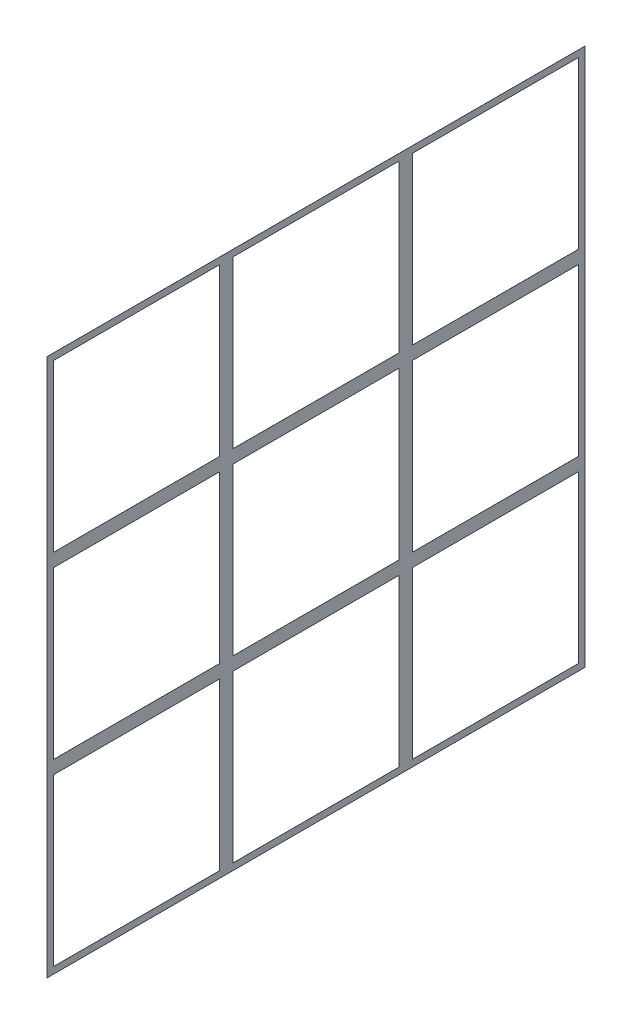
SolidWorks part; units mm, degrees
ref_plane "前视基准面" through (0, 0, 0) normal (0, 0, 1) x (1, 0, 0)
ref_plane "上视基准面" through (0, 0, 0) normal (0, 1, 0) x (1, 0, 0)
ref_plane "右视基准面" through (0, 0, 0) normal (1, 0, 0) x (0, 0, -1)
other "Configuration Table"
sketch "草图1" plane through (0, 0, 0) normal (1, 0, 0) x (0, 0, -1)
  line L0 (-290, 290) -> (-250, 290) construction
  line L1 (-810, 810) -> (810, 810)
  line L2 (-810, 810) -> (-810, -810)
  line L3 (-810, -810) -> (810, -810)
  line L4 (810, 810) -> (810, -810)
  line L5 (-790, 790) -> (-290, 790)
  line L6 (-790, 790) -> (-790, 290)
  line L7 (-790, 290) -> (-290, 290)
  line L8 (-290, 790) -> (-290, 290)
  line L9 (-250, 790) -> (250, 790)
  line L10 (-250, 790) -> (-250, 290)
  line L11 (-250, 290) -> (250, 290)
  line L12 (250, 790) -> (250, 290)
  line L13 (290, 790) -> (790, 790)
  line L14 (290, 790) -> (290, 290)
  line L15 (290, 290) -> (790, 290)
  line L16 (790, 790) -> (790, 290)
  line L17 (790, 250) -> (290, 250)
  line L18 (790, 250) -> (790, -250)
  line L19 (790, -250) -> (290, -250)
  line L20 (290, 250) -> (290, -250)
  line L21 (-250, 250) -> (250, 250)
  line L22 (-250, 250) -> (-250, -250)
  line L23 (-250, -250) -> (250, -250)
  line L24 (250, 250) -> (250, -250)
  line L25 (-790, 250) -> (-290, 250)
  line L26 (-790, 250) -> (-790, -250)
  line L27 (-790, -250) -> (-290, -250)
  line L28 (-290, 250) -> (-290, -250)
  line L29 (-790, -290) -> (-290, -290)
  line L30 (-790, -290) -> (-790, -790)
  line L31 (-790, -790) -> (-290, -790)
  line L32 (-290, -290) -> (-290, -790)
  line L33 (-250, -290) -> (250, -290)
  line L34 (-250, -290) -> (-250, -790)
  line L35 (-250, -790) -> (250, -790)
  line L36 (250, -290) -> (250, -790)
  line L37 (290, -290) -> (790, -290)
  line L38 (290, -290) -> (290, -790)
  line L39 (290, -790) -> (790, -790)
  line L40 (790, -290) -> (790, -790)
  line L41 (250, 290) -> (290, 290) construction
  line L42 (-290, 290) -> (-290, 250) construction
  line L43 (-290, -250) -> (-290, -290) construction
  line L44 (-790, 790) -> (-810, 790) construction
  line L45 (-790, 790) -> (-790, 810) construction
  line L46 (790, -790) -> (810, -790) construction
  line L47 (790, -790) -> (790, -810) construction
  dimension "D1" = 810
  dimension "D2" = 810
  dimension "D3" = 1620
  dimension "D4" = 20
  dimension "D5" = 40
extrude "凸台-拉伸1" add sketch "草图1" along normal blind 0.1
